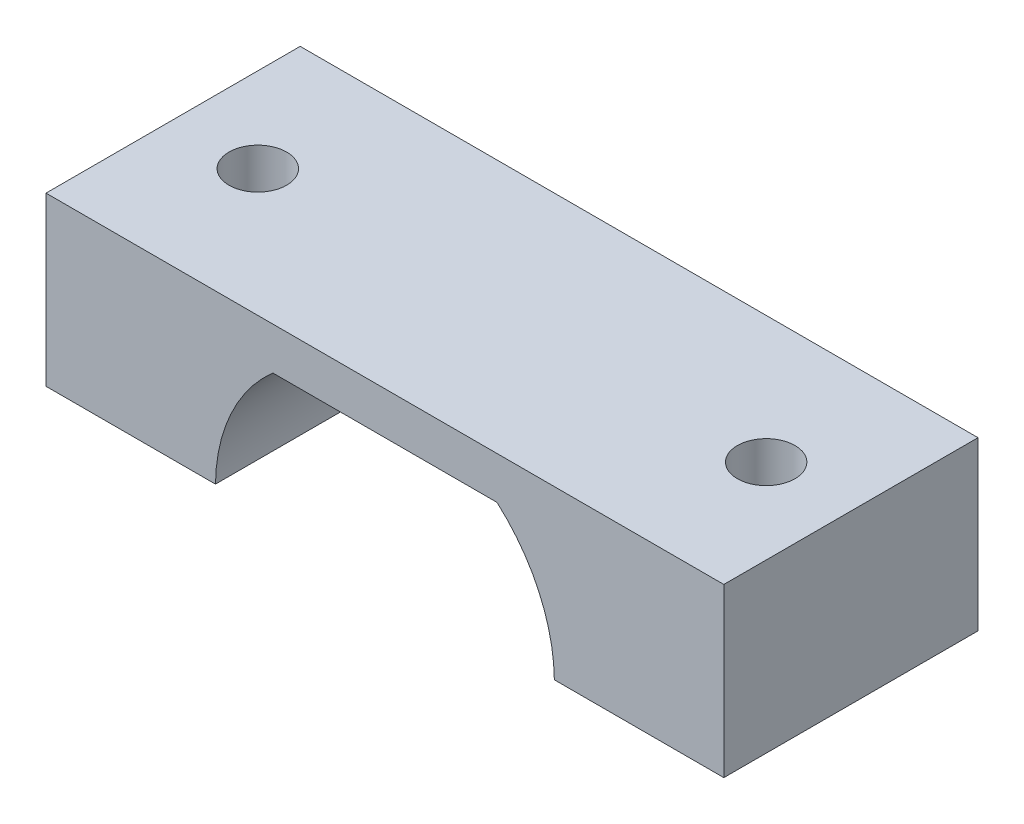
SolidWorks part; units mm, degrees
material "ABS"
ref_plane "Front Plane" through (0, 0, 0) normal (0, 0, 1) x (1, 0, 0)
ref_plane "Top Plane" through (0, 0, 0) normal (0, 1, 0) x (1, 0, 0)
ref_plane "Right Plane" through (0, 0, 0) normal (1, 0, 0) x (0, 0, -1)
sketch "Motor Clamp Outline Sketch" plane through (0, 0, 0) normal (0, 0, 1) x (1, 0, 0)
  line L0 (-20, 0.125) -> (-9.9992, 0.125)
  line L1 (-20, 10) -> (20, 10) construction
  line L2 (-20, 10) -> (-20, 0) construction
  line L3 (-20, 0) -> (20, 0) construction
  line L4 (20, 10) -> (20, 0) construction
  line L5 (-20, 10) -> (20, 0) construction
  line L6 (-20, 0) -> (20, 10) construction
  line L7 (-20, 0.125) -> (-20, 10)
  line L8 (-20, 10) -> (20, 10)
  line L9 (20, 10) -> (20, 0.125)
  line L10 (9.9992, 0.125) -> (20, 0.125)
  line L11 (-6.6144, 7.5) -> (6.6144, 7.5)
  line L12 (-20, 0.125) -> (20, 0.125) construction
  arc A0 (9.9992, 0.125) -> (-9.9992, 0.125) centre (0, 0) ccw construction
  arc A1 (9.9992, 0.125) -> (6.6144, 7.5) centre (0, 0) ccw
  arc A2 (-6.6144, 7.5) -> (-9.9992, 0.125) centre (0, 0) ccw
  point P3 (0, 5)
  dimension "D2" = 20
  dimension "D1" = 40
  dimension "D3" = 10
  dimension "D5" = 2.5
  dimension "D4" = 0.125
extrude "Motor Clamp Outline Solid" add sketch "Motor Clamp Outline Sketch" along normal mid plane 15
sketch "Motor Clamp Mounting Holes Sketch" plane through (0, 10, 0) normal (0, 1, 0) x (1, 0, 0)
  line L0 (-15, 0) -> (15, 0) construction
  circle A0 centre (-15, 0) radius 1.7
  circle A1 centre (15, 0) radius 1.7
  point P4 (0, 0)
  dimension "D1" = 3.4
  dimension "D2" = 30
extrude "Motor Clamp Mounting Hole Cut" cut sketch "Motor Clamp Mounting Holes Sketch" against normal through all
